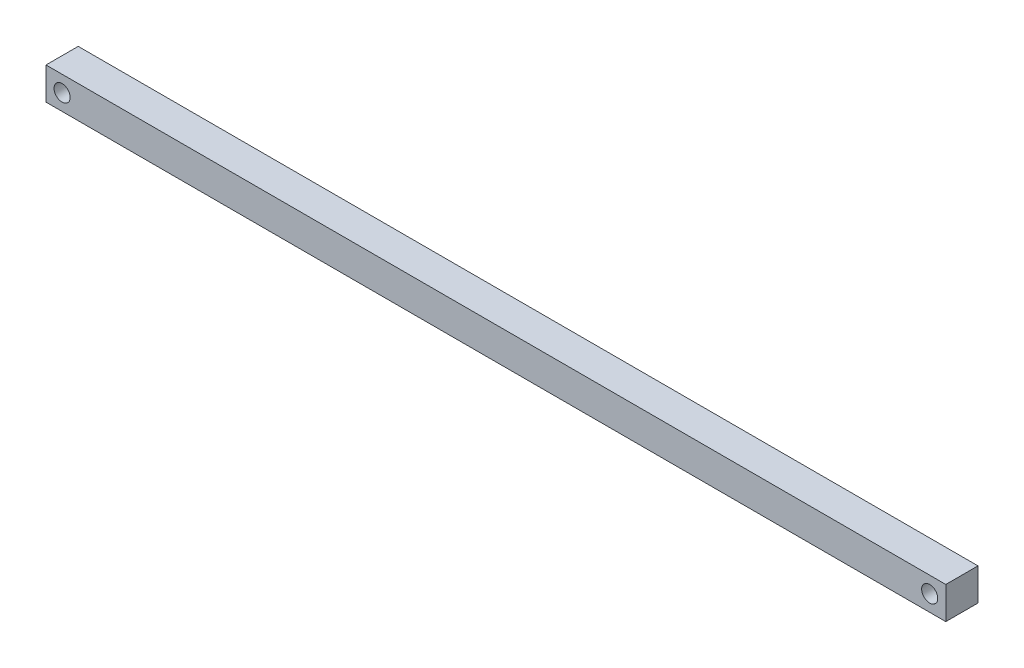
SolidWorks part; units mm, degrees
material "1060 Alloy for 162A"
ref_plane "Front Plane" through (0, 0, 0) normal (0, 0, 1) x (1, 0, 0)
ref_plane "Top Plane" through (0, 0, 0) normal (0, 1, 0) x (1, 0, 0)
ref_plane "Right Plane" through (0, 0, 0) normal (1, 0, 0) x (0, 0, -1)
sketch "Sketch1" plane through (0, 0, 0) normal (0, 0, 1) x (1, 0, 0)
  line L0 (404, 0) -> (-404, 0) construction
  line L1 (419, 15) -> (-419, 15)
  line L2 (419, 15) -> (419, -15)
  line L3 (419, -15) -> (-419, -15)
  line L4 (-419, 15) -> (-419, -15)
  line L5 (419, 15) -> (-419, -15) construction
  line L6 (419, -15) -> (-419, 15) construction
  circle A0 centre (-404, 0) radius 7.5
  circle A1 centre (404, 0) radius 7.5
  point P0 (0, 0)
  point P8 (0, 0)
  dimension "D2" = 15
  dimension "D1" = 30
  dimension "D3" = 808
  dimension "D4" = 15
extrude "Boss-Extrude1" add sketch "Sketch1" along normal mid plane 30
equation "\"A\"= 202"
equation "\"hole_diameter\"=15"
equation "\"D2@Sketch1\"=\"hole_diameter\""
equation "\"D3@Sketch1\"=4*\"A\""
equation "\"D4@Sketch1\"=\"hole_diameter\""
